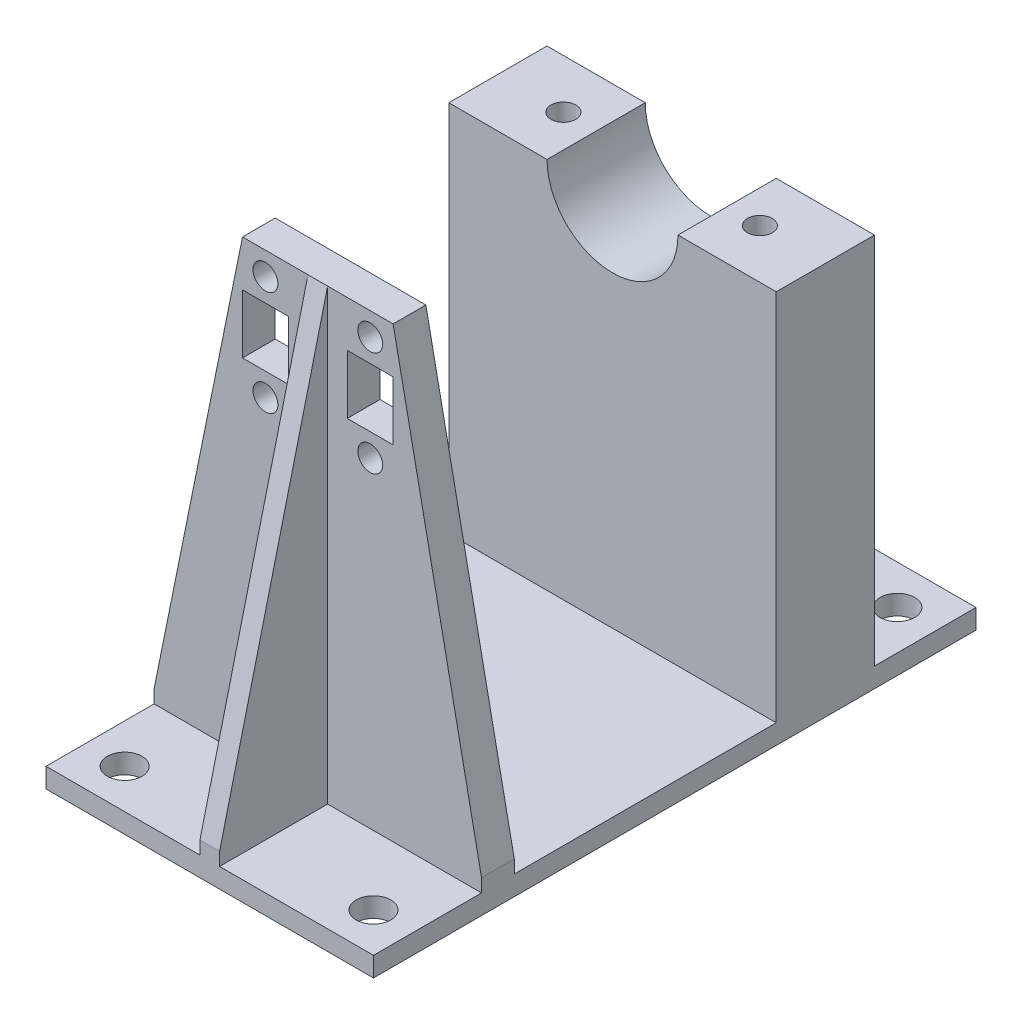
SolidWorks part; units mm, degrees
material "ABS"
ref_plane "Front Plane" through (0, 0, 0) normal (0, 0, 1) x (1, 0, 0)
ref_plane "Top Plane" through (0, 0, 0) normal (0, 1, 0) x (1, 0, 0)
ref_plane "Right Plane" through (0, 0, 0) normal (1, 0, 0) x (0, 0, -1)
sketch "Mouting Mount Sketch" plane through (0, 0, 0) normal (0, 0, 1) x (1, 0, 0)
  line L1 (25, -55) -> (-25, -55)
  line L2 (25, -55) -> (25, 0)
  line L3 (25, 0) -> (-25, 0)
  line L4 (-25, -55) -> (-25, 0)
  line L5 (25, -55) -> (-25, 0) construction
  line L6 (25, 0) -> (-25, -55) construction
  circle A0 centre (0, 0) radius 10
  point P3 (0, -27.5)
  dimension "D1" = 20
  dimension "D2" = 50
  dimension "D3" = 55
extrude "Motor Mount Solid" add sketch "Mouting Mount Sketch" along normal mid plane 15 contours A0 L3 L4 L1 L2
sketch "Encoder Distance Sketch" plane through (0, -55, 0) normal (0, -1, 0) x (1, 0, 0)
  line L0 (25, 7.5) -> (25, -7.5) construction
  line L1 (-25, 7.5) -> (25, 7.5)
  line L2 (-25, 7.5) -> (-25, 47.5)
  line L3 (-25, 47.5) -> (25, 47.5)
  line L4 (25, 7.5) -> (25, 47.5)
  line L5 (-25, -7.5) -> (25, -7.5) construction
  line L6 (-25, -7.5) -> (-25, 52.5) construction
  line L7 (-25, 52.5) -> (25, 52.5) construction
  line L8 (25, -7.5) -> (25, 52.5) construction
  line M9 (-25, -7.5) -> (25, -7.5)
  line M10 (25, -7.5) -> (25, 7.5)
  line M11 (25, 7.5) -> (-25, 7.5)
  line M12 (-25, 7.5) -> (-25, -7.5)
  dimension "D1" = 40
  dimension "D2" = 5
extrude "Encoder Distance Solid" add sketch "Encoder Distance Sketch" along normal blind 5 contours M12 M9 M10 M11 | L4 L3 L2 M11 | L3 L8 L7 L6
sketch "Encoder Mount Sketch" plane through (0, 0, 47.5) normal (0, 0, 1) x (1, 0, 0)
  line L0 (-25, -60) -> (-25, -55)
  line L1 (-8, -8) -> (8, -8) construction
  line L2 (-8, -8) -> (-8, 8) construction
  line L3 (-8, 8) -> (8, 8) construction
  line L4 (8, -8) -> (8, 8) construction
  line L5 (-8, -8) -> (8, 8) construction
  line L6 (-8, 8) -> (8, -8) construction
  line L7 (-11.5, -11.5) -> (11.5, -11.5) construction
  line L8 (-11.5, -11.5) -> (-11.5, 11.5) construction
  line L9 (-11.5, 11.5) -> (11.5, 11.5)
  line L10 (11.5, -11.5) -> (11.5, 11.5) construction
  line L11 (-11.5, -11.5) -> (11.5, 11.5) construction
  line L12 (-11.5, 11.5) -> (11.5, -11.5) construction
  line L13 (-11.5, 4.5) -> (-4.5, 4.5)
  line L14 (-11.5, 4.5) -> (-11.5, -4.5)
  line L15 (-11.5, -4.5) -> (-4.5, -4.5)
  line L16 (-4.5, 4.5) -> (-4.5, -4.5)
  line L17 (-11.5, 4.5) -> (-4.5, -4.5) construction
  line L18 (-11.5, -4.5) -> (-4.5, 4.5) construction
  line L19 (4.5, 4.5) -> (11.5, 4.5)
  line L20 (4.5, 4.5) -> (4.5, -4.5)
  line L21 (4.5, -4.5) -> (11.5, -4.5)
  line L22 (11.5, 4.5) -> (11.5, -4.5)
  line L23 (4.5, 4.5) -> (11.5, -4.5) construction
  line L24 (4.5, -4.5) -> (11.5, 4.5) construction
  line L25 (-25, -55) -> (-11.5, 11.5)
  line L26 (-25, -60) -> (25, -60)
  line L27 (25, -60) -> (25, -55)
  line L28 (25, -55) -> (11.5, 11.5)
  circle A0 centre (-8, 8) radius 1.9
  circle A1 centre (8, 8) radius 1.9
  circle A2 centre (-8, -8) radius 1.9
  circle A3 centre (8, -8) radius 1.9
  circle A4 centre (8, 8) radius 3.5 construction
  circle A5 centre (-8, 8) radius 3.5 construction
  circle A6 centre (-8, -8) radius 3.5 construction
  circle A7 centre (8, -8) radius 3.5 construction
  point P0 (0, 0)
  point P14 (0, 0)
  point P19 (-8, 0)
  point P24 (8, 0)
  dimension "D2" = 3.8
  dimension "D3" = 7
  dimension "D1" = 16
extrude "Encoder Mount Solid" add sketch "Encoder Mount Sketch" along normal blind 5
sketch "Motor Clamp Mounting Holes Sketch" plane through (0, 0, 0) normal (0, 1, 0) x (1, 0, 0)
  line L0 (-15, 0) -> (15, 0) construction
  circle A0 centre (-15, 0) radius 1.9
  circle A1 centre (15, 0) radius 1.9
  point P4 (0, 0)
  dimension "D2" = 3.8
  dimension "D1" = 30
extrude "Motor Clamp Mounting Holes Cut" cut sketch "Motor Clamp Mounting Holes Sketch" against normal blind 16
sketch "Gusset Plate Sketch" plane through (0, 0, 52.5) normal (0, 0, 1) x (1, 0, 0)
  line L1 (-25, -55) -> (25, -55)
  line L2 (-25, -55) -> (-25, -60)
  line L3 (-25, -60) -> (25, -60)
  line L4 (25, -55) -> (25, -60)
extrude "Gusset Plate Solid" add sketch "Gusset Plate Sketch" along normal blind 16.5
sketch "Gusset Sketch" plane through (0, 0, 0) normal (1, 0, 0) x (0, 0, -1)
  line L0 (-52.5, 11.5) -> (-69, -55)
  line L1 (-69, -55) -> (-52.5, -55)
  line L2 (-52.5, -55) -> (-52.5, 11.5)
extrude "Gusset Solid" add sketch "Gusset Sketch" along normal mid plane 3
sketch "Mounting Plate Sketch" plane through (0, -55, 0) normal (0, 1, 0) x (1, 0, 0)
  line L0 (25, -7.5) -> (25, -47.5) construction
  line L1 (-25, -69) -> (25, -69)
  line L2 (-25, -69) -> (-25, 23)
  line L3 (-25, 23) -> (25, 23)
  line L4 (25, -69) -> (25, 23)
  line L5 (-19, -63) -> (19, -63) construction
  line L6 (-19, 17) -> (19, 17) construction
  circle A0 centre (-19, -63) radius 2.65
  circle A1 centre (19, -63) radius 6 construction
  circle A2 centre (19, -63) radius 2.65
  circle A3 centre (-19, -63) radius 6 construction
  circle A4 centre (-19, 17) radius 6 construction
  circle A5 centre (19, 17) radius 6 construction
  circle A6 centre (-19, 17) radius 2.65
  circle A7 centre (19, 17) radius 2.65
  point P10 (0, -63)
  point P18 (0, 17)
  dimension "D1" = 12
  dimension "D2" = 5.3
  dimension "D3" = 80
extrude "Mounting Plate Solid" add sketch "Mounting Plate Sketch" against normal up to surface (5 mm away) up to face at (0, -60, 30.75)
sketch "Mounting Hole Sketch" plane through (0, -55, 0) normal (0, 1, 0) x (1, 0, 0)
  line L0 (25, 23) -> (25, -69) construction
  line L3 (25, -23) -> (-25, -23) construction
  line L4 (-25, -47.5) -> (-25, -7.5) construction
  circle A0 centre (-19, 17) radius 2.65
  circle A1 centre (19, 17) radius 2.65
  circle A3 centre (19, -63) radius 2.65
  circle A4 centre (-19, -63) radius 2.65
  circle A5 centre (-19, 17) radius 2.65 construction
extrude "Mounting Holes Cut" cut sketch "Mounting Hole Sketch" against normal through all both and the other way through all contours A3 | A4 | A1 | A0
sketch "Mounting Plate Trim Sketch" plane through (0, -55, 0) normal (0, 1, 0) x (1, 0, 0)
  line L1 (-25, 23) -> (25, 23)
  line L2 (-25, 23) -> (-25, 7.5)
  line L3 (-25, 7.5) -> (25, 7.5)
  line L4 (25, 23) -> (25, 7.5)
  line L5 (-25, -7.5) -> (25, -7.5)
  line L6 (-25, -7.5) -> (-25, -47.5)
  line L7 (-25, -47.5) -> (25, -47.5)
  line L8 (25, -7.5) -> (25, -47.5)
  line L9 (1.5, -52.5) -> (25, -52.5)
  line L10 (1.5, -52.5) -> (1.5, -69)
  line L11 (1.5, -69) -> (25, -69)
  line L12 (25, -52.5) -> (25, -69)
  line L13 (-1.5, -52.5) -> (-25, -52.5)
  line L14 (-1.5, -52.5) -> (-1.5, -69)
  line L15 (-1.5, -69) -> (-25, -69)
  line L16 (-25, -52.5) -> (-25, -69)
extrude "Mounting Plate Trim Cut" cut sketch "Mounting Plate Trim Sketch" against normal blind 2
